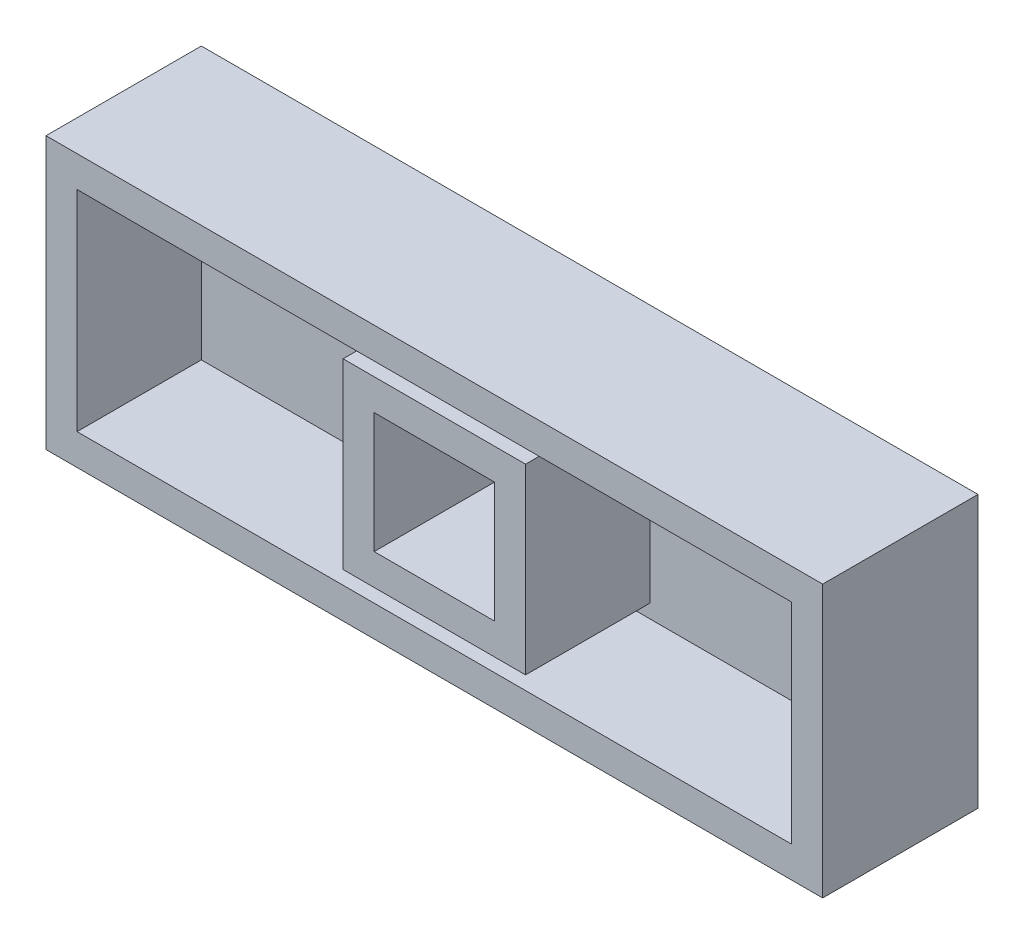
SolidWorks part; units mm, degrees
ref_plane "Front Plane" through (0, 0, 0) normal (0, 0, 1) x (1, 0, 0)
ref_plane "Top Plane" through (0, 0, 0) normal (0, 1, 0) x (1, 0, 0)
ref_plane "Right Plane" through (0, 0, 0) normal (1, 0, 0) x (0, 0, -1)
sketch "Sketch1" plane through (0, 0, 0) normal (0, 0, 1) x (1, 0, 0)
  line L1 (0, 0) -> (3.1, 0)
  line L2 (0, 0) -> (0, 3.1)
  line L3 (0, 3.1) -> (3.1, 3.1)
  line L4 (3.1, 0) -> (3.1, 3.1)
  line L5 (-8.45, -1.95) -> (11.55, -1.95)
  line L6 (-8.45, -1.95) -> (-8.45, 5.05)
  line L7 (-8.45, 5.05) -> (11.55, 5.05)
  line L8 (11.55, -1.95) -> (11.55, 5.05)
  point P9 (1.55, 5.05)
  point P10 (1.55, 3.1)
  point P11 (11.55, 1.55)
  point P12 (3.1, 1.55)
  dimension "D1" = 3.1
  dimension "D2" = 3.1
  dimension "D3" = 7
  dimension "D4" = 20
extrude "Boss-Extrude1" add sketch "Sketch1" along normal blind 4
shell "Shell1" thickness 0.8
